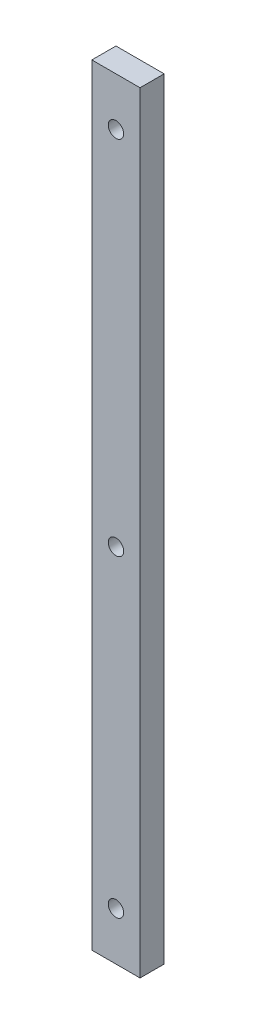
SolidWorks part; units mm, degrees
ref_plane "Plan de face" through (0, 0, 0) normal (0, 0, 1) x (1, 0, 0)
ref_plane "Plan de dessus" through (0, 0, 0) normal (0, 1, 0) x (1, 0, 0)
ref_plane "Plan de droite" through (0, 0, 0) normal (1, 0, 0) x (0, 0, -1)
sketch "Esquisse1" plane through (0, 0, 0) normal (0, 0, 1) x (1, 0, 0)
  line L0 (5, 160) -> (5, 0) construction
  line L1 (0, 0) -> (10, 0)
  line L2 (0, 0) -> (0, 160)
  line L3 (0, 160) -> (10, 160)
  line L4 (10, 0) -> (10, 160)
  line L5 (0, 80) -> (10, 80) construction
  circle A0 centre (5, 10) radius 1.6
  circle A1 centre (5, 150) radius 1.6
  circle A2 centre (5, 75) radius 1.6
  dimension "D3" = 3.2
  dimension "D1" = 160
  dimension "D2" = 10
  dimension "D4" = 10
  dimension "D5" = 75
extrude "Boss.-Extru.1" add sketch "Esquisse1" along normal blind 5
